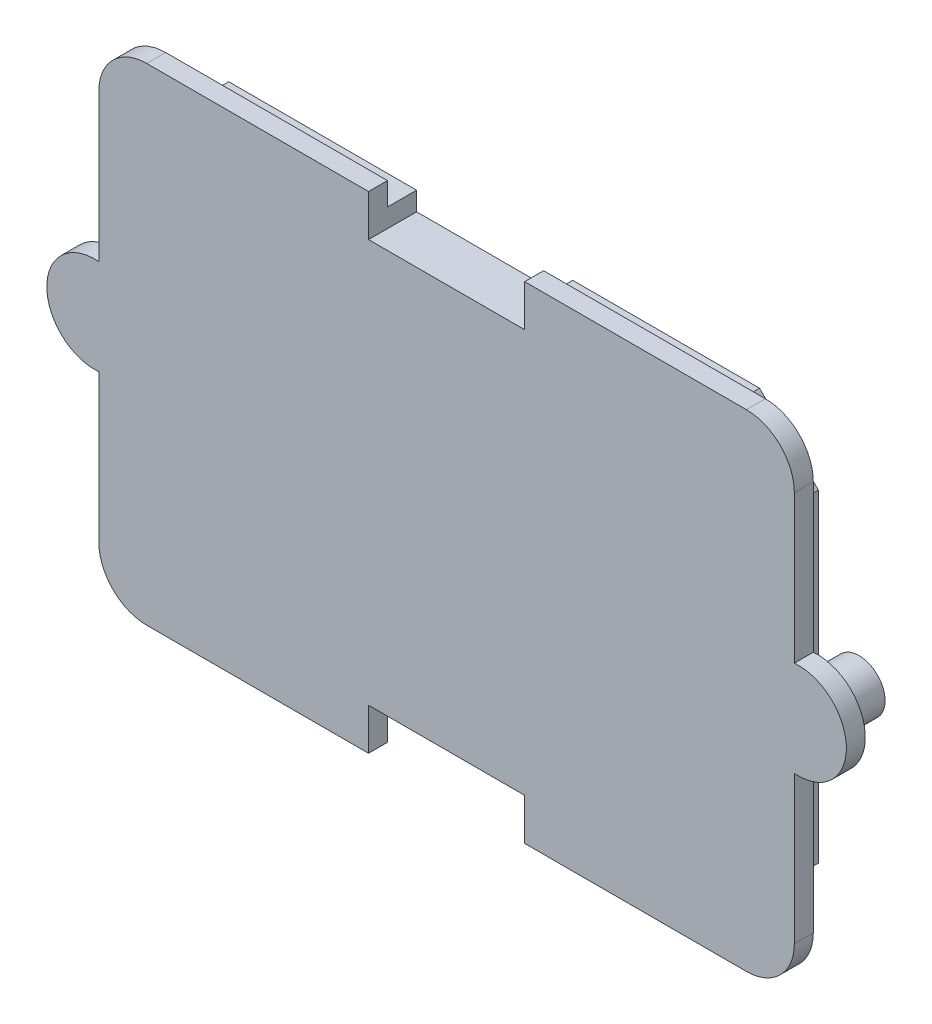
SolidWorks part; units mm, degrees
material "PET"
ref_plane "Front Plane" through (0, 0, 0) normal (0, 0, 1) x (1, 0, 0)
ref_plane "Top Plane" through (0, 0, 0) normal (0, 1, 0) x (1, 0, 0)
ref_plane "Right Plane" through (0, 0, 0) normal (1, 0, 0) x (0, 0, -1)
sketch "Sketch1" plane through (0, 0, 0) normal (0, 0, 1) x (1, 0, 0)
  line L6 (21.4725, 3.175) -> (21.4725, 11.9225) construction
  line L7 (21.4725, -11.9225) -> (21.4725, -3.175) construction
  line L8 (-18.2975, -15.0975) -> (18.2975, -15.0975) construction
  line L9 (-21.4725, -3.175) -> (-21.4725, -11.9225) construction
  line L10 (-21.4725, 3.175) -> (-21.4725, 11.9225) construction
  line L11 (18.2975, 15.0975) -> (-18.2975, 15.0975) construction
  line L12 (-21.4725, 0) -> (21.4725, 0) construction
  line L13 (0, 15.0975) -> (0, -15.0975) construction
  arc A6 (21.4725, 11.9225) -> (18.2975, 15.0975) centre (18.2975, 11.9225) ccw construction
  arc A7 (21.4725, -3.175) -> (21.4725, 3.175) centre (21.4725, 0) ccw construction
  arc A8 (18.2975, -15.0975) -> (21.4725, -11.9225) centre (18.2975, -11.9225) ccw construction
  arc A9 (-21.4725, -11.9225) -> (-18.2975, -15.0975) centre (-18.2975, -11.9225) ccw construction
  arc A10 (-21.4725, 3.175) -> (-21.4725, -3.175) centre (-21.4725, 0) ccw construction
  arc A11 (-18.2975, 15.0975) -> (-21.4725, 11.9225) centre (-18.2975, 11.9225) ccw construction
  dimension "D1" = 3.175
  dimension "D2" = 21.4725
  dimension "D3" = 15.0975
sketch "Sketch2" plane through (0, 0, 0) normal (0, 0, 1) x (1, 0, 0)
  line L53 (21.2185, 2.9099) -> (21.2185, 11.9225)
  line L54 (21.2185, -11.9225) -> (21.2185, -2.9099)
  line L55 (-18.2975, -14.8435) -> (18.2975, -14.8435)
  line L56 (-21.2185, -2.9099) -> (-21.2185, -11.9225)
  line L57 (-21.2185, 11.9225) -> (-21.2185, 2.9099)
  line L58 (18.2975, 14.8435) -> (-18.2975, 14.8435)
  line L59 (21.2185, 2.9099) -> (21.2185, 11.9225)
  line L60 (21.2185, -11.9225) -> (21.2185, -2.9099)
  line L61 (-18.2975, -14.8435) -> (18.2975, -14.8435)
  line L62 (-21.2185, -2.9099) -> (-21.2185, -11.9225)
  line L63 (-21.2185, 11.9225) -> (-21.2185, 2.9099)
  line L64 (18.2975, 14.8435) -> (-18.2975, 14.8435)
  arc A42 (21.2185, 11.9225) -> (18.2975, 14.8435) centre (18.2975, 11.9225) ccw
  arc A43 (21.2185, -2.9099) -> (21.2185, 2.9099) centre (21.4725, 0) ccw
  arc A44 (18.2975, -14.8435) -> (21.2185, -11.9225) centre (18.2975, -11.9225) ccw
  arc A45 (-21.2185, -11.9225) -> (-18.2975, -14.8435) centre (-18.2975, -11.9225) ccw
  arc A46 (-21.2185, 2.9099) -> (-21.2185, -2.9099) centre (-21.4725, 0) ccw
  arc A47 (-18.2975, 14.8435) -> (-21.2185, 11.9225) centre (-18.2975, 11.9225) ccw
  arc A48 (21.2185, 11.9225) -> (18.2975, 14.8435) centre (18.2975, 11.9225) ccw
  arc A49 (21.2185, -2.9099) -> (21.2185, 2.9099) centre (21.4725, 0) ccw
  arc A50 (18.2975, -14.8435) -> (21.2185, -11.9225) centre (18.2975, -11.9225) ccw
  arc A51 (-21.2185, -11.9225) -> (-18.2975, -14.8435) centre (-18.2975, -11.9225) ccw
  arc A52 (-21.2185, 2.9099) -> (-21.2185, -2.9099) centre (-21.4725, 0) ccw
  arc A53 (-18.2975, 14.8435) -> (-21.2185, 11.9225) centre (-18.2975, 11.9225) ccw
  dimension "D1" = 0.254
extrude "Boss-Extrude1" add sketch "Sketch2" along normal blind 1.5875
sketch "Sketch3" plane through (0, 0, 1.5875) normal (0, 0, 1) x (1, 0, 0)
  line L0 (-18.2975, -14.8435) -> (18.2975, -14.8435) construction
  line L1 (-4.7625, -14.8435) -> (4.7625, -14.8435)
  line L2 (-4.7625, -14.8435) -> (-4.7625, -12.3035)
  line L3 (-4.7625, -12.3035) -> (4.7625, -12.3035)
  line L4 (4.7625, -14.8435) -> (4.7625, -12.3035)
  line L5 (0, 0) -> (0, -12.3035) construction
  line L6 (18.2975, 14.8435) -> (-18.2975, 14.8435) construction
  line L7 (4.7625, 14.8435) -> (-4.7625, 14.8435)
  line L8 (4.7625, 14.8435) -> (4.7625, 12.3035)
  line L9 (4.7625, 12.3035) -> (-4.7625, 12.3035)
  line L10 (-4.7625, 14.8435) -> (-4.7625, 12.3035)
  dimension "D1" = 2.54
  dimension "D2" = 9.525
extrude "Cut-Extrude1" cut sketch "Sketch3" against normal through all
sketch "Sketch4" plane through (0, 0, 0) normal (0, 0, -1) x (-1, 0, 0)
  line L0 (-21.4725, 0) -> (0, 0) construction
  line L1 (0, 0) -> (21.4725, 0) construction
  circle A0 centre (-21.4725, 0) radius 1.5875
  circle A1 centre (21.4725, 0) radius 1.5875
  arc A2 (-21.2185, 2.9099) -> (-21.2185, -2.9099) centre (-21.4725, 0) ccw construction
  arc A3 (21.2185, -2.9099) -> (21.2185, 2.9099) centre (21.4725, 0) ccw construction
  dimension "D1" = 3.175
  dimension "D2" = 3.175
extrude "Boss-Extrude2" add sketch "Sketch4" along normal blind 2.54
sketch "Sketch5" plane through (0, 0, 0) normal (0, 0, -1) x (-1, 0, 0)
  line L1 (-19.885, 13.51) -> (19.885, 13.51) construction
  line L2 (-19.885, 13.51) -> (-19.885, -13.51) construction
  line L3 (-19.885, -13.51) -> (19.885, -13.51) construction
  line L4 (19.885, 13.51) -> (19.885, -13.51) construction
  line L5 (0, 0) -> (0, 13.51) construction
  line L6 (-19.885, 0) -> (0, 0) construction
  line L7 (-19.758, 9.8544) -> (-16.1659, 13.4465)
  line L8 (-16.1659, 13.4465) -> (-4.7625, 13.4465)
  line L9 (-4.7625, 13.4465) -> (-4.7625, 12.3035)
  line L10 (-4.7625, 12.3035) -> (4.7625, 12.3035)
  line L11 (4.7625, 12.3035) -> (4.7625, 13.4465)
  line L12 (4.7625, 13.4465) -> (16.2294, 13.4465)
  line L13 (16.2294, 13.4465) -> (19.8215, 9.8544)
  line L14 (19.8215, 9.8544) -> (19.8215, -9.8544)
  line L18 (19.8215, -9.8544) -> (16.2294, -13.4465)
  line L19 (16.2294, -13.4465) -> (4.7625, -13.4465)
  line L20 (4.7625, -13.4465) -> (4.7625, -12.3035)
  line L21 (4.7625, -12.3035) -> (-4.7625, -12.3035)
  line L22 (-4.7625, -12.3035) -> (-4.7625, -13.4465)
  line L24 (-4.7625, -13.4465) -> (-16.1659, -13.4465)
  line L25 (-16.1659, -13.4465) -> (-19.758, -9.8544)
  line L29 (-19.758, -9.8544) -> (-19.758, 9.8544)
  line L30 (4.7625, 14.8435) -> (4.7625, 12.3035) construction
  line L31 (4.7625, -12.3035) -> (4.7625, -14.8435) construction
  point P4 (-19.885, -8.234)
  point P5 (17.9393, -12.5772)
  point P21 (4.7625, -12.3035)
  point P22 (0, 0)
  point P31 (-4.7625, -13.2141)
  point P32 (-17.4218, -13.081)
  point P33 (-17.4038, 13.51)
  point P35 (-19.885, -11.4877)
  point P36 (-19.885, 10.9397)
  point P37 (-4.7625, 12.3035)
  point P39 (4.7625, 12.3035)
  point P41 (-19.3905, -11.5934)
  point P42 (-18.0083, 13.1862)
  point P43 (4.7625, 13.1394)
  point P44 (4.7625, 13.2358)
  point P47 (4.7625, -13.0203)
  point P50 (19.1449, 1.2186)
  point P51 (19.1449, 11.4819)
  point P52 (19.511, -11.26)
  point P54 (16.2294, -13.51)
  dimension "D1" = 27.02
  dimension "D2" = 39.77
  dimension "D3" = 0.254
  dimension "D4" = 0.127
  dimension "D5" = 0.127
  dimension "D6" = 0.127
  dimension "D7" = 135
  dimension "D8" = 5.08
  dimension "D9" = 135
extrude "Boss-Extrude3" add sketch "Sketch5" along normal blind 1.778
sketch "Sketch6" plane through (0, 0, 0) normal (0, 1, 0) x (1, 0, 0)
  line L0 (24.3935, -1.5875) -> (24.3935, 0) construction
  line L1 (-24.3935, -1.5875) -> (24.3935, -1.5875)
  line L2 (-24.3935, -1.5875) -> (-24.3935, -1.1557)
  line L3 (-24.3935, -1.1557) -> (24.3935, -1.1557)
  line L4 (24.3935, -1.5875) -> (24.3935, -1.1557)
  point P5 (24.3935, -1.1771)
  dimension "D1" = 0.4318
extrude "Cut-Extrude2" cut sketch "Sketch6" against normal mid plane 38.1
